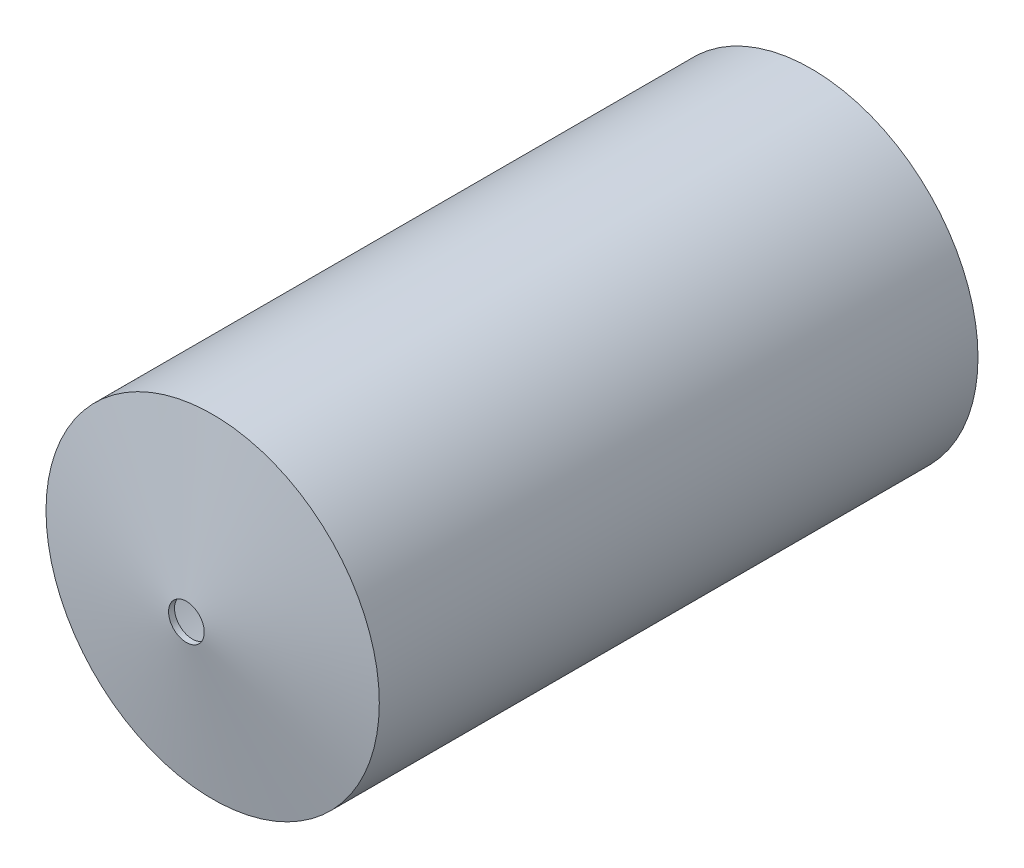
SolidWorks part; units mm, degrees
ref_plane "Front Plane" through (0, 0, 0) normal (0, 0, 1) x (1, 0, 0)
ref_plane "Top Plane" through (0, 0, 0) normal (0, 1, 0) x (1, 0, 0)
ref_plane "Right Plane" through (0, 0, 0) normal (1, 0, 0) x (0, 0, -1)
sketch "Sketch1" plane through (0, 0, 0) normal (0, 1, 0) x (1, 0, 0)
  line L0 (3.81, 0) -> (0, 0) construction
  line L1 (0, 0) -> (0, 133.35) construction
  line L2 (0, 133.35) -> (34.29, 133.35) construction
  line L3 (3.81, 0) -> (35.56, 5.5984)
  line L4 (35.56, 5.5984) -> (35.56, 133.35)
  line L5 (35.56, 5.5984) -> (0, 5.5984) construction
  line L6 (34.29, 133.35) -> (35.56, 133.35)
  line L7 (34.29, 133.35) -> (34.29, 6.6444)
  line L8 (34.29, 6.6444) -> (3.81, 1.27)
  line L9 (3.81, 1.27) -> (3.81, 0)
  dimension "D1" = 3.81
  dimension "D2" = 133.35
  dimension "D3" = 35.56
  dimension "D4" = 1.27
  dimension "D5" = 1.27
  dimension "D6" = 10
revolve "Revolve1" add sketch "Sketch1" angle 360 about L1
